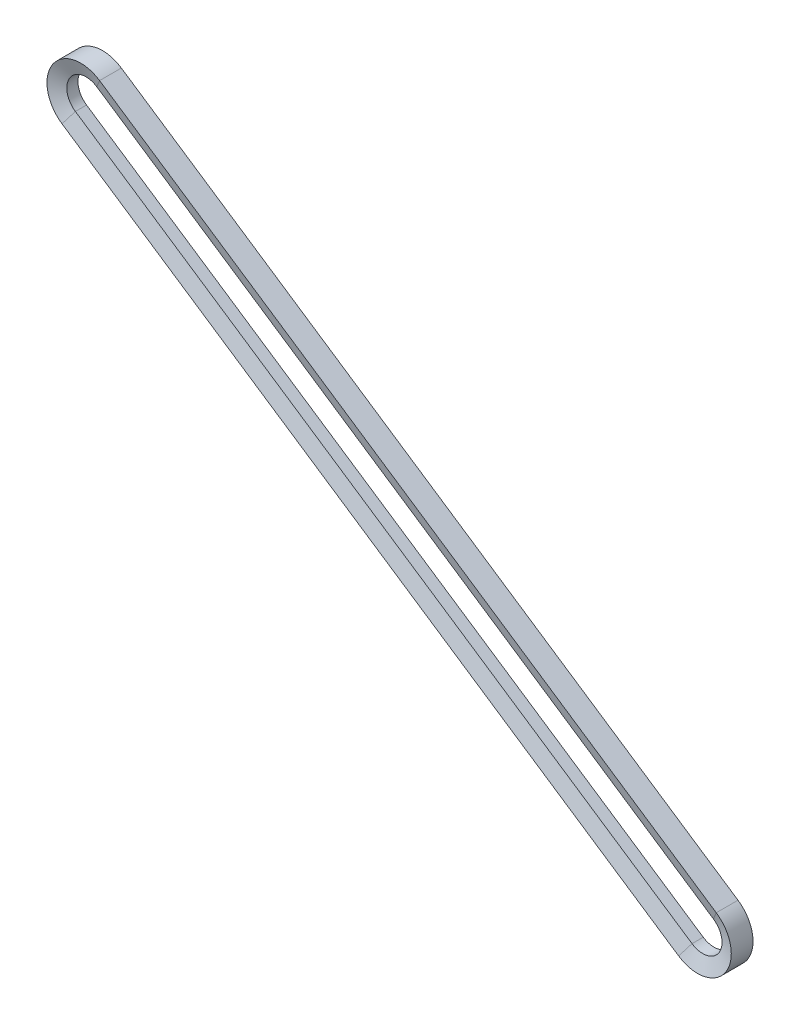
SolidWorks part; units mm, degrees
ref_plane "前视基准面" through (0, 0, 0) normal (0, 0, 1) x (1, 0, 0)
ref_plane "上视基准面" through (0, 0, 0) normal (0, 1, 0) x (1, 0, 0)
ref_plane "右视基准面" through (0, 0, 0) normal (1, 0, 0) x (0, 0, -1)
sketch "草图2" plane through (0, 0, 0) normal (0, 0, 1) x (1, 0, 0)
  line L0 (0, 0) -> (1, 0) construction
  line L1 (0, 0) -> (0, 1) construction
  line L2 (2.9461, 4.4057) -> (172.5417, -109.0012)
  line L3 (166.6496, -117.8126) -> (-2.9461, -4.4057)
  arc A0 (-2.9461, -4.4057) -> (2.9461, 4.4057) centre (0, 0) cw
  arc A1 (172.5417, -109.0012) -> (166.6496, -117.8126) centre (169.5956, -113.4069) cw
ref_plane "基准面4" through (169.5956, -113.4069, 0) normal (0.8313, -0.5559, 0) x (0, 0, -1)
sketch "草图3" plane through (169.5956, -113.4069, 0) normal (0.8313, -0.5559, 0) x (0, 0, -1)
  line L0 (-1.535, 5.3) -> (1.535, 5.3)
  line L1 (0, 5.3) -> (0, -5.3) construction
  line L2 (0, 5.3) -> (0, -5.3) construction
  line L3 (1.535, 5.3) -> (2.9909, 9.3)
  line L4 (2.9909, 9.3) -> (-2.9909, 9.3)
  line L5 (0, 9.3) -> (0, 5.3)
  line L6 (-1.535, 5.3) -> (-2.9909, 9.3)
  dimension "D1" = 110
  dimension "D2" = 4
sweep "扫描1" add profiles "草图3" path "草图2"
